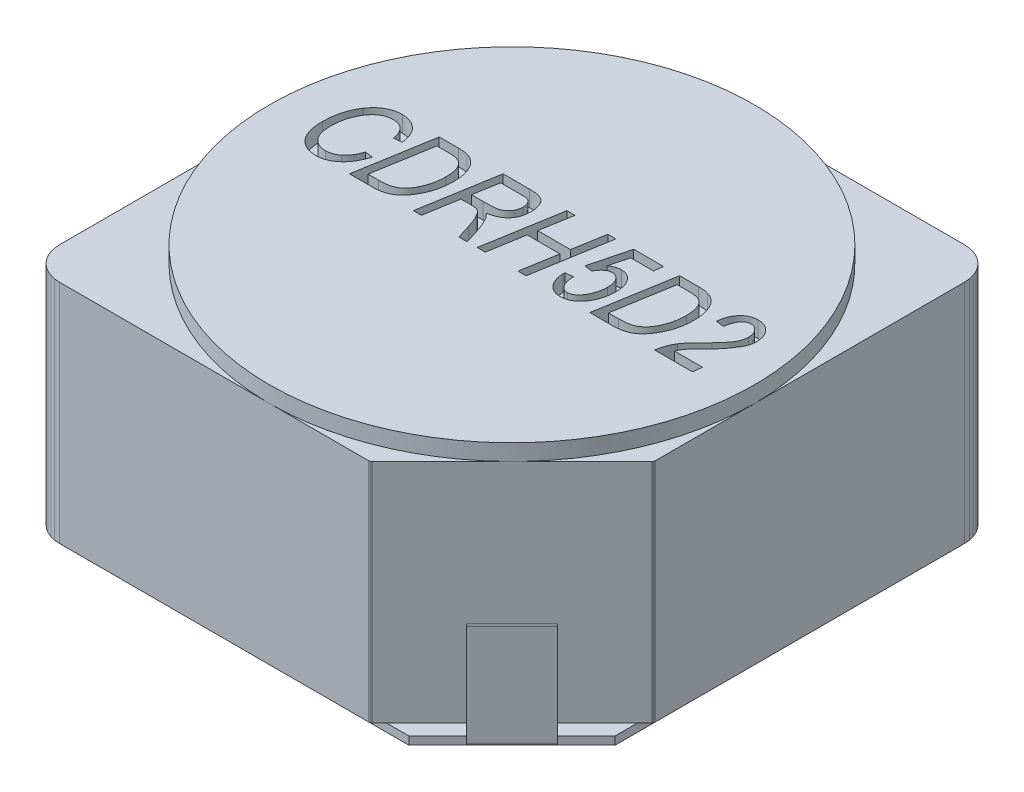
SolidWorks part; units mm, degrees
ref_plane "Спереди" through (0, 0, 0) normal (0, 0, 1) x (1, 0, 0)
ref_plane "Сверху" through (0, 0, 0) normal (0, 1, 0) x (1, 0, 0)
ref_plane "Справа" through (0, 0, 0) normal (1, 0, 0) x (0, 0, -1)
sketch "Эскиз2" plane through (0, 0, 0) normal (0, 1, 0) x (1, 0, 0)
  line L64 (0.1013, -4.0003) -> (0.93, -4.0003)
  line L65 (0.93, -4.0003) -> (1.0622, -4.2371)
  line L66 (1.0622, -4.2371) -> (1.2213, -4.4568)
  line L67 (1.2213, -4.4568) -> (1.4051, -4.6562)
  line L68 (1.4051, -4.6562) -> (1.6112, -4.8326)
  line L69 (1.6112, -4.8326) -> (1.8365, -4.9835)
  line L70 (1.8365, -4.9835) -> (2.0781, -5.1069)
  line L71 (2.0781, -5.1069) -> (2.3326, -5.2009)
  line L72 (2.3326, -5.2009) -> (2.5963, -5.2643)
  line L73 (2.5963, -5.2643) -> (2.8656, -5.2962)
  line L74 (2.8656, -5.2962) -> (3.1369, -5.2962)
  line L75 (3.1369, -5.2962) -> (3.4062, -5.2643)
  line L76 (3.4062, -5.2643) -> (3.67, -5.2009)
  line L77 (3.67, -5.2009) -> (3.9244, -5.1069)
  line L78 (3.9244, -5.1069) -> (4.166, -4.9835)
  line L79 (4.166, -4.9835) -> (4.3914, -4.8326)
  line L80 (4.3914, -4.8326) -> (4.5974, -4.6562)
  line L81 (4.5974, -4.6562) -> (4.7813, -4.4568)
  line L82 (4.7813, -4.4568) -> (4.9404, -4.2371)
  line L83 (4.9404, -4.2371) -> (5.0725, -4.0003)
  line L84 (5.0725, -4.0003) -> (5.9013, -4.0003)
  line L85 (5.9013, -4.0003) -> (5.9013, -4.6281)
  line L86 (5.9013, -4.6281) -> (5.5477, -4.9816)
  line L87 (5.5477, -4.9816) -> (5.5588, -4.9927)
  line L88 (5.5588, -4.9927) -> (5.5696, -5.0035)
  line L89 (5.5696, -5.0035) -> (5.0045, -5.5685)
  line L90 (5.0045, -5.5685) -> (4.9937, -5.5578)
  line L91 (4.9937, -5.5578) -> (4.9827, -5.5467)
  line L92 (4.9827, -5.5467) -> (4.6291, -5.9003)
  line L93 (4.6291, -5.9003) -> (1.1013, -5.9003)
  line L94 (1.1013, -5.9003) -> (0.1013, -4.9003)
  line L95 (0.1013, -4.9003) -> (0.1013, -4.0003)
  line L96 (0.4437, -1.0078) -> (0.433, -0.997)
  line L97 (0.433, -0.997) -> (0.998, -0.432)
  line L98 (0.998, -0.432) -> (1.0088, -0.4427)
  line L99 (1.0088, -0.4427) -> (1.0199, -0.4538)
  line L100 (1.0199, -0.4538) -> (1.3734, -0.1003)
  line L101 (1.3734, -0.1003) -> (4.9013, -0.1003)
  line L102 (4.9013, -0.1003) -> (5.9013, -1.1003)
  line L103 (5.9013, -1.1003) -> (5.9013, -2.0003)
  line L104 (5.9013, -2.0003) -> (5.0725, -2.0003)
  line L105 (5.0725, -2.0003) -> (4.9404, -1.7634)
  line L106 (4.9404, -1.7634) -> (4.7813, -1.5437)
  line L107 (4.7813, -1.5437) -> (4.5974, -1.3443)
  line L108 (4.5974, -1.3443) -> (4.3914, -1.1679)
  line L109 (4.3914, -1.1679) -> (4.166, -1.017)
  line L110 (4.166, -1.017) -> (3.9244, -0.8936)
  line L111 (3.9244, -0.8936) -> (3.67, -0.7996)
  line L112 (3.67, -0.7996) -> (3.4062, -0.7362)
  line L113 (3.4062, -0.7362) -> (3.1369, -0.7043)
  line L114 (3.1369, -0.7043) -> (2.8656, -0.7043)
  line L115 (2.8656, -0.7043) -> (2.5963, -0.7362)
  line L116 (2.5963, -0.7362) -> (2.3326, -0.7996)
  line L117 (2.3326, -0.7996) -> (2.0781, -0.8936)
  line L118 (2.0781, -0.8936) -> (1.8365, -1.017)
  line L119 (1.8365, -1.017) -> (1.6112, -1.1679)
  line L120 (1.6112, -1.1679) -> (1.4051, -1.3443)
  line L121 (1.4051, -1.3443) -> (1.2213, -1.5437)
  line L122 (1.2213, -1.5437) -> (1.0622, -1.7634)
  line L123 (1.0622, -1.7634) -> (0.93, -2.0003)
  line L124 (0.93, -2.0003) -> (0.1013, -2.0003)
  line L125 (0.1013, -2.0003) -> (0.1013, -1.3724)
  line L126 (0.1013, -1.3724) -> (0.4548, -1.0189)
  line L127 (0.4548, -1.0189) -> (0.4437, -1.0078)
  point P0 (0.6662, -1.4853)
  point P1 (0.2196, -2.9483)
  point P2 (-1.0143, -2.406)
extrude "Бобышка-Вытянуть1" add sketch "Эскиз2" along normal blind 0.1 separate body contours L127 L126 L125 L124 L123 L122 L121 L120 L119 L118 L117 L116 L115 L114 L113 L112 L111 L110 L109 L108 L107 L106 L105 L104 L103 L102 L101 L100 L99 L98 L97 L96 | L69 L70 L71 L72 L73 L74 L75 L76 L77 L78 L79 L80 L81 L82 L83 L84 L85 L86 L87 L88 L89 L90 L91 L92 L93 L94 L95 L64 L65 L66 L67 L68
sketch "Эскиз3" plane through (0, 0.1, 0) normal (0, 1, 0) x (1, 0, 0)
  line L0 (0.1013, -1.6553) -> (1.6563, -0.1003)
  line L1 (4.3463, -5.9003) -> (5.9013, -4.3453)
  line L202 (1.7416, -0.0149) -> (1.6563, -0.1003)
  line L203 (1.7476, -0.0098) -> (1.7416, -0.0149)
  line L204 (1.7543, -0.0057) -> (1.7476, -0.0098)
  line L205 (1.7615, -0.0027) -> (1.7543, -0.0057)
  line L206 (1.7691, -0.0009) -> (1.7615, -0.0027)
  line L207 (1.777, -0.0003) -> (1.7691, -0.0009)
  line L208 (5.6013, -0.0003) -> (1.777, -0.0003)
  line L209 (5.6638, -0.0052) -> (5.6013, -0.0003)
  line L210 (5.7249, -0.0198) -> (5.6638, -0.0052)
  line L211 (5.7829, -0.0438) -> (5.7249, -0.0198)
  line L212 (5.8364, -0.0766) -> (5.7829, -0.0438)
  line L213 (5.8841, -0.1174) -> (5.8364, -0.0766)
  line L214 (5.9249, -0.1651) -> (5.8841, -0.1174)
  line L215 (5.9577, -0.2187) -> (5.9249, -0.1651)
  line L216 (5.9817, -0.2766) -> (5.9577, -0.2187)
  line L217 (5.9963, -0.3377) -> (5.9817, -0.2766)
  line L218 (6.0013, -0.4003) -> (5.9963, -0.3377)
  line L219 (6.0013, -4.2245) -> (6.0013, -0.4003)
  line L220 (6.0006, -4.2324) -> (6.0013, -4.2245)
  line L221 (5.9988, -4.24) -> (6.0006, -4.2324)
  line L222 (5.9958, -4.2472) -> (5.9988, -4.24)
  line L223 (5.9917, -4.2539) -> (5.9958, -4.2472)
  line L224 (5.9866, -4.2599) -> (5.9917, -4.2539)
  line L225 (5.9013, -4.3453) -> (5.9866, -4.2599)
  line L251 (4.2609, -5.9856) -> (4.3463, -5.9003)
  line L252 (4.2549, -5.9907) -> (4.2609, -5.9856)
  line L253 (4.2482, -5.9948) -> (4.2549, -5.9907)
  line L254 (4.241, -5.9978) -> (4.2482, -5.9948)
  line L255 (4.2334, -5.9996) -> (4.241, -5.9978)
  line L256 (4.2255, -6.0003) -> (4.2334, -5.9996)
  line L257 (0.4013, -6.0003) -> (4.2255, -6.0003)
  line L258 (0.3387, -5.9953) -> (0.4013, -6.0003)
  line L259 (0.2776, -5.9807) -> (0.3387, -5.9953)
  line L260 (0.2197, -5.9567) -> (0.2776, -5.9807)
  line L261 (0.1661, -5.9239) -> (0.2197, -5.9567)
  line L262 (0.1184, -5.8831) -> (0.1661, -5.9239)
  line L263 (0.0776, -5.8354) -> (0.1184, -5.8831)
  line L264 (0.0449, -5.7818) -> (0.0776, -5.8354)
  line L265 (0.0208, -5.7239) -> (0.0449, -5.7818)
  line L266 (0.0062, -5.6628) -> (0.0208, -5.7239)
  line L267 (0.0013, -5.6003) -> (0.0062, -5.6628)
  line L268 (0.0013, -1.776) -> (0.0013, -5.6003)
  line L269 (0.0019, -1.7681) -> (0.0013, -1.776)
  line L270 (0.0037, -1.7605) -> (0.0019, -1.7681)
  line L271 (0.0067, -1.7533) -> (0.0037, -1.7605)
  line L272 (0.0108, -1.7466) -> (0.0067, -1.7533)
  line L273 (0.0159, -1.7406) -> (0.0108, -1.7466)
  line L274 (0.1013, -1.6553) -> (0.0159, -1.7406)
extrude "Бобышка-Вытянуть2" add sketch "Эскиз3" along normal blind 2.8
sketch "Эскиз4" plane through (0, 0.1, 0) normal (0, 1, 0) x (1, 0, 0)
  line L0 (0.4548, -1.0189) -> (1.0199, -0.4538)
  line L1 (4.9827, -5.5467) -> (5.5477, -4.9816)
  line L19 (4.9827, -5.5467) -> (5.0045, -5.5685)
  line L20 (5.0045, -5.5685) -> (5.5696, -5.0035)
  line L21 (5.5696, -5.0035) -> (5.5477, -4.9816)
  line L36 (1.0199, -0.4538) -> (0.998, -0.432)
  line L37 (0.998, -0.432) -> (0.433, -0.997)
  line L38 (0.433, -0.997) -> (0.4548, -1.0189)
extrude "Бобышка-Вытянуть3" add sketch "Эскиз4" along normal blind 1.2
fillet "Скругление1" radius 0.05 1 edges at (5.287, 0, 5.286)
fillet "Скругление2" radius 0.05 1 edges at (0.7155, 0, 0.7145)
sketch "Эскиз5" plane through (0, 2.9, 0) normal (0, 1, 0) x (1, 0, 0)
  line L0 (6.0013, -4.2245) -> (6.0013, -0.4003) construction
  line L1 (0, 0) -> (6.0013, 0) construction
  line L2 (0, 0) -> (0, -6.0003) construction
  line L3 (0, -6.0003) -> (6.0013, -6.0003) construction
  line L4 (6.0013, 0) -> (6.0013, -6.0003) construction
  line L5 (0, 0) -> (6.0013, -6.0003) construction
  line L7 (6.0013, 0) -> (0, -6.0003) construction
  circle A0 centre (3.0006, -3.0001) radius 3.0006
extrude "Бобышка-Вытянуть4" add sketch "Эскиз5" along normal blind 0.2
sketch "Эскиз6" plane through (0, 3.1, 0) normal (0, 1, 0) x (1, 0, 0)
  line L0 (0.396, -3.2446) -> (5.3754, -3.2446) construction
  text T0 "CDRH5D28" font "Arial Narrow" height 0.95
extrude "Вырез-Вытянуть1" cut sketch "Эскиз6" against normal blind 0.2
